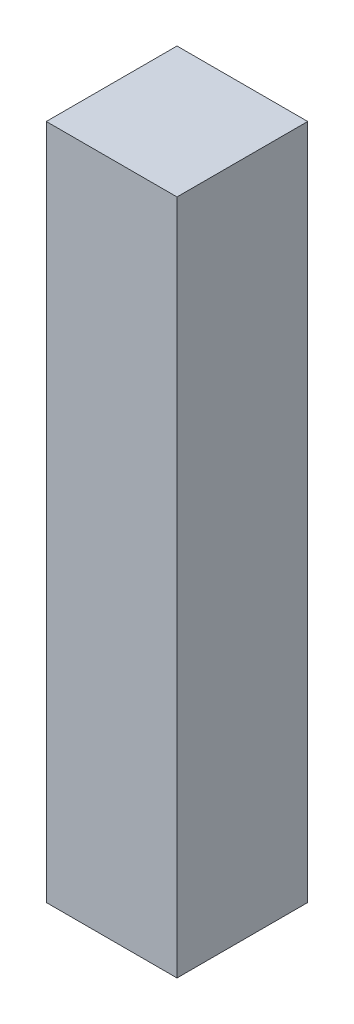
SolidWorks part; units mm, degrees
ref_plane "Front Plane" through (0, 0, 0) normal (0, 0, 1) x (1, 0, 0)
ref_plane "Top Plane" through (0, 0, 0) normal (0, 1, 0) x (1, 0, 0)
ref_plane "Right Plane" through (0, 0, 0) normal (1, 0, 0) x (0, 0, -1)
sketch "Sketch1" plane through (0, 0, 0) normal (0, 1, 0) x (1, 0, 0)
  line L1 (0, 0) -> (75, 0)
  line L2 (0, 0) -> (0, 75)
  line L3 (0, 75) -> (75, 75)
  line L4 (75, 0) -> (75, 75)
  dimension "D1" = 75
  dimension "D2" = 75
extrude "Boss-Extrude1" add sketch "Sketch1" along normal blind 388.112
